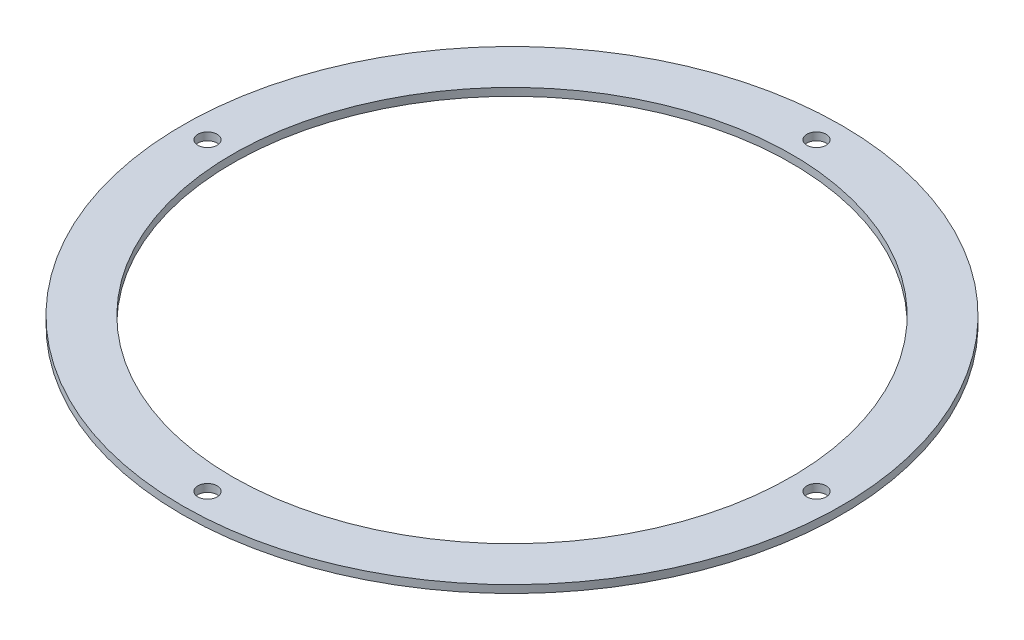
SolidWorks part; units mm, degrees
ref_plane "前视基准面" through (0, 0, 0) normal (0, 0, 1) x (1, 0, 0)
ref_plane "上视基准面" through (0, 0, 0) normal (0, 1, 0) x (1, 0, 0)
ref_plane "右视基准面" through (0, 0, 0) normal (1, 0, 0) x (0, 0, -1)
other "Configuration Table"
sketch "草图1" plane through (0, 0, 0) normal (0, 1, 0) x (1, 0, 0)
  line L0 (0, 0) -> (0, 101)
  line L1 (0, 85.5) -> (0, 72.5)
  line L2 (0, 85.5) -> (0, 101)
  circle A0 centre (0, 0) radius 72.5
  circle A1 centre (0, 0) radius 85.5
  circle A2 centre (0, 0) radius 101
  circle A3 centre (0, 79) radius 2.5
  circle A4 centre (79, 0) radius 2.5
  circle A5 centre (0, -79) radius 2.5
  circle A6 centre (-79, 0) radius 2.5
  circle A7 centre (0, 93.25) radius 2.5
  circle A8 centre (93.25, 0) radius 2.5
  circle A9 centre (0, -93.25) radius 2.5
  circle A10 centre (-93.25, 0) radius 2.5
  point P20 (0, 0)
  point P29 (0, 0)
  dimension "D1" = 145
  dimension "D3" = 202
  dimension "D4" = 5
  dimension "D5" = 5
  dimension "D2" = 13
extrude "凸台-拉伸1" add sketch "草图1" along normal blind 2
sketch "草图2" plane through (0, 0, 0) normal (0, -1, 0) x (1, 0, 0)
  line L0 (0, 0) -> (0, 50000)
  line L1 (0, 0) -> (35355.3391, 35355.3391)
  line L2 (0, 0) -> (35355.3391, -35355.3391)
  circle A1 centre (0, 0) radius 72.5
  circle A2 centre (0, 0) radius 85.5
